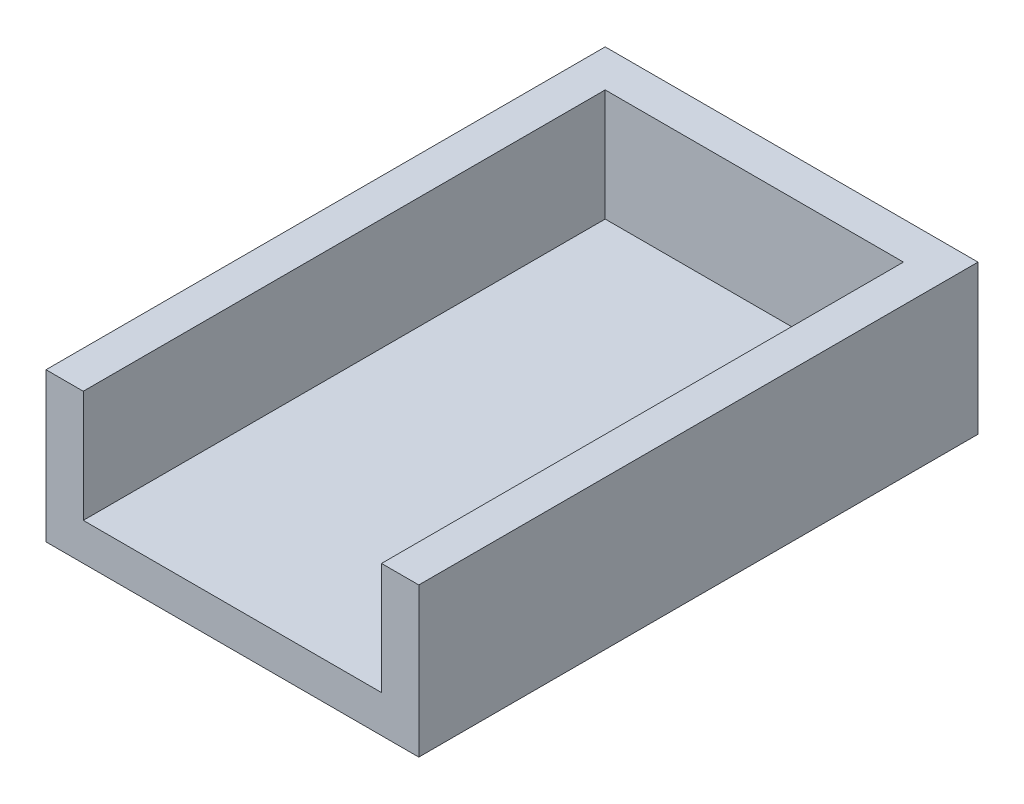
SolidWorks part; units mm, degrees
ref_plane "Front Plane" through (0, 0, 0) normal (0, 0, 1) x (1, 0, 0)
ref_plane "Top Plane" through (0, 0, 0) normal (0, 1, 0) x (1, 0, 0)
ref_plane "Right Plane" through (0, 0, 0) normal (1, 0, 0) x (0, 0, -1)
sketch "Sketch1" plane through (0, 0, 0) normal (0, 1, 0) x (1, 0, 0)
  line L9 (-50, -75) -> (50, -75)
  line L10 (-50, -75) -> (-50, 75)
  line L11 (-50, 75) -> (50, 75)
  line L12 (50, -75) -> (50, 75)
  line L13 (-50, -75) -> (50, 75) construction
  line L14 (-50, 75) -> (50, -75) construction
  point P0 (0, 0)
  dimension "D1" = 150
  dimension "D2" = 100
extrude "Boss-Extrude1" add sketch "Sketch1" along normal blind 40
sketch "Sketch2" plane through (0, 40, 0) normal (0, 1, 0) x (1, 0, 0)
  line L1 (-40, -65) -> (40, -65)
  line L2 (-40, -65) -> (-40, 65)
  line L3 (-40, 65) -> (40, 65)
  line L4 (40, -65) -> (40, 65)
  line L5 (-40, -65) -> (40, 65) construction
  line L6 (-40, 65) -> (40, -65) construction
  point P0 (0, 0)
  dimension "D1" = 130
  dimension "D2" = 80
extrude "Cut-Extrude1" cut sketch "Sketch2" against normal blind 30
sketch "Sketch3" plane through (0, 0, 75) normal (0, 0, 1) x (1, 0, 0)
  line L1 (-50, 0) -> (50, 0)
  line L2 (-50, 0) -> (-50, 40)
  line L3 (-50, 40) -> (50, 40)
  line L4 (50, 0) -> (50, 40)
  line L5 (-40, 10) -> (40, 10)
  line L6 (-40, 10) -> (-40, 40)
  line L7 (-40, 40) -> (40, 40)
  line L8 (40, 10) -> (40, 40)
  dimension "D1" = 80
  dimension "D2" = 10
  dimension "D3" = 10
extrude "Cut-Extrude2" cut sketch "Sketch3" against normal blind 30 contours L5 L8 L3 L6
